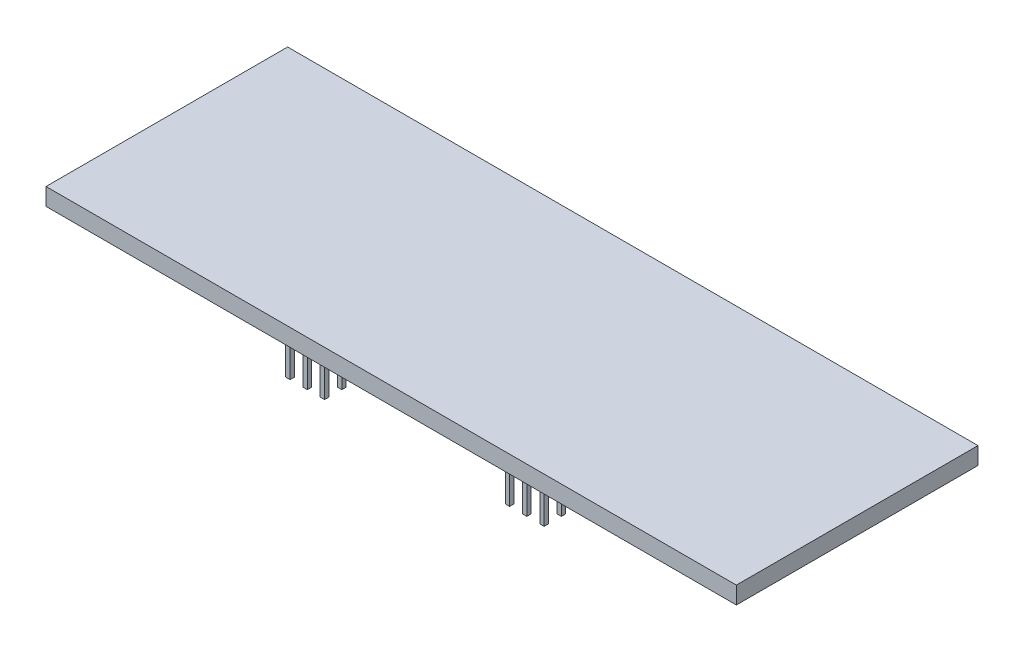
SolidWorks part; units mm, degrees
ref_plane "Front Plane" through (0, 0, 0) normal (0, 0, 1) x (1, 0, 0)
ref_plane "Top Plane" through (0, 0, 0) normal (0, 1, 0) x (1, 0, 0)
ref_plane "Right Plane" through (0, 0, 0) normal (1, 0, 0) x (0, 0, -1)
sketch "Sketch1" plane through (0, 0, 0) normal (0, 1, 0) x (1, 0, 0)
  line L0 (50.8, 35.56) -> (50.8, 0) construction
  line L1 (0, 0) -> (101.6, 0)
  line L2 (0, 0) -> (0, 35.56)
  line L3 (0, 35.56) -> (101.6, 35.56)
  line L4 (101.6, 0) -> (101.6, 35.56)
  point P5 (50.8, 35.56)
  dimension "D1" = 35.56
  dimension "D2" = 101.6
extrude "Boss-Extrude1" add sketch "Sketch1" along normal blind 2.54
sketch "Sketch2" plane through (0, 0, 0) normal (0, -1, 0) x (1, 0, 0)
  line L0 (0, -35.56) -> (0, 0) construction
  line L1 (30.8356, -2.54) -> (38.4556, -2.54)
  line L2 (30.8356, -2.54) -> (30.8356, -33.02)
  line L3 (30.8356, -33.02) -> (38.4556, -33.02)
  line L4 (38.4556, -2.54) -> (38.4556, -33.02)
  line L5 (0, 0) -> (101.6, 0) construction
  line L6 (0, 0) -> (50.8, 0) construction
  line L7 (50.8, 0) -> (50.8, -35.56) construction
  line L8 (101.6, -35.56) -> (0, -35.56) construction
  line L9 (63.1444, -2.54) -> (63.1444, -33.02)
  line L10 (70.7644, -33.02) -> (63.1444, -33.02)
  line L11 (70.7644, -2.54) -> (70.7644, -33.02)
  line L12 (70.7644, -2.54) -> (63.1444, -2.54)
  point P4 (30.8356, -17.78)
  point P5 (0, -17.78)
  point P6 (50.8, 0)
  point P9 (34.6456, -2.54)
  point P15 (25.4, 0)
  point P23 (76.2, 0)
  point P24 (66.9544, -2.54)
  point P25 (70.7644, -17.78)
  dimension "D1" = 7.62
  dimension "D2" = 30.48
  dimension "D3" = 12.3444
extrude "Boss-Extrude2" add sketch "Sketch2" along normal blind 2.54
sketch "Sketch3" plane through (0, -2.54, 0) normal (0, -1, 0) x (1, 0, 0)
  line L0 (38.4556, -2.54) -> (30.8356, -2.54) construction
  line L1 (31.7881, -3.4925) -> (32.4231, -3.4925)
  line L2 (31.7881, -3.4925) -> (31.7881, -4.1275)
  line L3 (31.7881, -4.1275) -> (32.4231, -4.1275)
  line L4 (32.4231, -3.4925) -> (32.4231, -4.1275)
  line L5 (30.8356, -2.54) -> (30.8356, -33.02) construction
  line L6 (34.3281, -3.4925) -> (34.9631, -3.4925)
  line L7 (34.3281, -3.4925) -> (34.3281, -4.1275)
  line L8 (34.3281, -4.1275) -> (34.9631, -4.1275)
  line L9 (34.9631, -3.4925) -> (34.9631, -4.1275)
  line L10 (36.8681, -3.4925) -> (37.5031, -3.4925)
  line L11 (36.8681, -3.4925) -> (36.8681, -4.1275)
  line L12 (36.8681, -4.1275) -> (37.5031, -4.1275)
  line L13 (37.5031, -3.4925) -> (37.5031, -4.1275)
  line L14 (31.7881, -6.0325) -> (32.4231, -6.0325)
  line L15 (31.7881, -6.0325) -> (31.7881, -6.6675)
  line L16 (31.7881, -6.6675) -> (32.4231, -6.6675)
  line L17 (32.4231, -6.0325) -> (32.4231, -6.6675)
  line L18 (34.3281, -6.0325) -> (34.9631, -6.0325)
  line L19 (34.3281, -6.0325) -> (34.3281, -6.6675)
  line L20 (34.3281, -6.6675) -> (34.9631, -6.6675)
  line L21 (34.9631, -6.0325) -> (34.9631, -6.6675)
  line L22 (36.8681, -6.0325) -> (37.5031, -6.0325)
  line L23 (36.8681, -6.0325) -> (36.8681, -6.6675)
  line L24 (36.8681, -6.6675) -> (37.5031, -6.6675)
  line L25 (37.5031, -6.0325) -> (37.5031, -6.6675)
  line L26 (31.7881, -8.5725) -> (32.4231, -8.5725)
  line L27 (31.7881, -8.5725) -> (31.7881, -9.2075)
  line L28 (31.7881, -9.2075) -> (32.4231, -9.2075)
  line L29 (32.4231, -8.5725) -> (32.4231, -9.2075)
  line L30 (34.3281, -8.5725) -> (34.9631, -8.5725)
  line L31 (34.3281, -8.5725) -> (34.3281, -9.2075)
  line L32 (34.3281, -9.2075) -> (34.9631, -9.2075)
  line L33 (34.9631, -8.5725) -> (34.9631, -9.2075)
  line L34 (36.8681, -8.5725) -> (37.5031, -8.5725)
  line L35 (36.8681, -8.5725) -> (36.8681, -9.2075)
  line L36 (36.8681, -9.2075) -> (37.5031, -9.2075)
  line L37 (37.5031, -8.5725) -> (37.5031, -9.2075)
  line L38 (31.7881, -11.1125) -> (32.4231, -11.1125)
  line L39 (31.7881, -11.1125) -> (31.7881, -11.7475)
  line L40 (31.7881, -11.7475) -> (32.4231, -11.7475)
  line L41 (32.4231, -11.1125) -> (32.4231, -11.7475)
  line L42 (34.3281, -11.1125) -> (34.9631, -11.1125)
  line L43 (34.3281, -11.1125) -> (34.3281, -11.7475)
  line L44 (34.3281, -11.7475) -> (34.9631, -11.7475)
  line L45 (34.9631, -11.1125) -> (34.9631, -11.7475)
  line L46 (36.8681, -11.1125) -> (37.5031, -11.1125)
  line L47 (36.8681, -11.1125) -> (36.8681, -11.7475)
  line L48 (36.8681, -11.7475) -> (37.5031, -11.7475)
  line L49 (37.5031, -11.1125) -> (37.5031, -11.7475)
  line L50 (31.7881, -13.6525) -> (32.4231, -13.6525)
  line L51 (31.7881, -13.6525) -> (31.7881, -14.2875)
  line L52 (31.7881, -14.2875) -> (32.4231, -14.2875)
  line L53 (32.4231, -13.6525) -> (32.4231, -14.2875)
  line L54 (34.3281, -13.6525) -> (34.9631, -13.6525)
  line L55 (34.3281, -13.6525) -> (34.3281, -14.2875)
  line L56 (34.3281, -14.2875) -> (34.9631, -14.2875)
  line L57 (34.9631, -13.6525) -> (34.9631, -14.2875)
  line L58 (36.8681, -13.6525) -> (37.5031, -13.6525)
  line L59 (36.8681, -13.6525) -> (36.8681, -14.2875)
  line L60 (36.8681, -14.2875) -> (37.5031, -14.2875)
  line L61 (37.5031, -13.6525) -> (37.5031, -14.2875)
  line L62 (31.7881, -16.1925) -> (32.4231, -16.1925)
  line L63 (31.7881, -16.1925) -> (31.7881, -16.8275)
  line L64 (31.7881, -16.8275) -> (32.4231, -16.8275)
  line L65 (32.4231, -16.1925) -> (32.4231, -16.8275)
  line L66 (34.3281, -16.1925) -> (34.9631, -16.1925)
  line L67 (34.3281, -16.1925) -> (34.3281, -16.8275)
  line L68 (34.3281, -16.8275) -> (34.9631, -16.8275)
  line L69 (34.9631, -16.1925) -> (34.9631, -16.8275)
  line L70 (36.8681, -16.1925) -> (37.5031, -16.1925)
  line L71 (36.8681, -16.1925) -> (36.8681, -16.8275)
  line L72 (36.8681, -16.8275) -> (37.5031, -16.8275)
  line L73 (37.5031, -16.1925) -> (37.5031, -16.8275)
  line L74 (31.7881, -18.7325) -> (32.4231, -18.7325)
  line L75 (31.7881, -18.7325) -> (31.7881, -19.3675)
  line L76 (31.7881, -19.3675) -> (32.4231, -19.3675)
  line L77 (32.4231, -18.7325) -> (32.4231, -19.3675)
  line L78 (34.3281, -18.7325) -> (34.9631, -18.7325)
  line L79 (34.3281, -18.7325) -> (34.3281, -19.3675)
  line L80 (34.3281, -19.3675) -> (34.9631, -19.3675)
  line L81 (34.9631, -18.7325) -> (34.9631, -19.3675)
  line L82 (36.8681, -18.7325) -> (37.5031, -18.7325)
  line L83 (36.8681, -18.7325) -> (36.8681, -19.3675)
  line L84 (36.8681, -19.3675) -> (37.5031, -19.3675)
  line L85 (37.5031, -18.7325) -> (37.5031, -19.3675)
  line L86 (31.7881, -21.2725) -> (32.4231, -21.2725)
  line L87 (31.7881, -21.2725) -> (31.7881, -21.9075)
  line L88 (31.7881, -21.9075) -> (32.4231, -21.9075)
  line L89 (32.4231, -21.2725) -> (32.4231, -21.9075)
  line L90 (34.3281, -21.2725) -> (34.9631, -21.2725)
  line L91 (34.3281, -21.2725) -> (34.3281, -21.9075)
  line L92 (34.3281, -21.9075) -> (34.9631, -21.9075)
  line L93 (34.9631, -21.2725) -> (34.9631, -21.9075)
  line L94 (36.8681, -21.2725) -> (37.5031, -21.2725)
  line L95 (36.8681, -21.2725) -> (36.8681, -21.9075)
  line L96 (36.8681, -21.9075) -> (37.5031, -21.9075)
  line L97 (37.5031, -21.2725) -> (37.5031, -21.9075)
  line L98 (31.7881, -23.8125) -> (32.4231, -23.8125)
  line L99 (31.7881, -23.8125) -> (31.7881, -24.4475)
  line L100 (31.7881, -24.4475) -> (32.4231, -24.4475)
  line L101 (32.4231, -23.8125) -> (32.4231, -24.4475)
  line L102 (34.3281, -23.8125) -> (34.9631, -23.8125)
  line L103 (34.3281, -23.8125) -> (34.3281, -24.4475)
  line L104 (34.3281, -24.4475) -> (34.9631, -24.4475)
  line L105 (34.9631, -23.8125) -> (34.9631, -24.4475)
  line L106 (36.8681, -23.8125) -> (37.5031, -23.8125)
  line L107 (36.8681, -23.8125) -> (36.8681, -24.4475)
  line L108 (36.8681, -24.4475) -> (37.5031, -24.4475)
  line L109 (37.5031, -23.8125) -> (37.5031, -24.4475)
  line L110 (31.7881, -26.3525) -> (32.4231, -26.3525)
  line L111 (31.7881, -26.3525) -> (31.7881, -26.9875)
  line L112 (31.7881, -26.9875) -> (32.4231, -26.9875)
  line L113 (32.4231, -26.3525) -> (32.4231, -26.9875)
  line L114 (34.3281, -26.3525) -> (34.9631, -26.3525)
  line L115 (34.3281, -26.3525) -> (34.3281, -26.9875)
  line L116 (34.3281, -26.9875) -> (34.9631, -26.9875)
  line L117 (34.9631, -26.3525) -> (34.9631, -26.9875)
  line L118 (36.8681, -26.3525) -> (37.5031, -26.3525)
  line L119 (36.8681, -26.3525) -> (36.8681, -26.9875)
  line L120 (36.8681, -26.9875) -> (37.5031, -26.9875)
  line L121 (37.5031, -26.3525) -> (37.5031, -26.9875)
  line L122 (31.7881, -28.8925) -> (32.4231, -28.8925)
  line L123 (31.7881, -28.8925) -> (31.7881, -29.5275)
  line L124 (31.7881, -29.5275) -> (32.4231, -29.5275)
  line L125 (32.4231, -28.8925) -> (32.4231, -29.5275)
  line L126 (34.3281, -28.8925) -> (34.9631, -28.8925)
  line L127 (34.3281, -28.8925) -> (34.3281, -29.5275)
  line L128 (34.3281, -29.5275) -> (34.9631, -29.5275)
  line L129 (34.9631, -28.8925) -> (34.9631, -29.5275)
  line L130 (36.8681, -28.8925) -> (37.5031, -28.8925)
  line L131 (36.8681, -28.8925) -> (36.8681, -29.5275)
  line L132 (36.8681, -29.5275) -> (37.5031, -29.5275)
  line L133 (37.5031, -28.8925) -> (37.5031, -29.5275)
  line L134 (31.7881, -31.4325) -> (32.4231, -31.4325)
  line L135 (31.7881, -31.4325) -> (31.7881, -32.0675)
  line L136 (31.7881, -32.0675) -> (32.4231, -32.0675)
  line L137 (32.4231, -31.4325) -> (32.4231, -32.0675)
  line L138 (34.3281, -31.4325) -> (34.9631, -31.4325)
  line L139 (34.3281, -31.4325) -> (34.3281, -32.0675)
  line L140 (34.3281, -32.0675) -> (34.9631, -32.0675)
  line L141 (34.9631, -31.4325) -> (34.9631, -32.0675)
  line L142 (36.8681, -31.4325) -> (37.5031, -31.4325)
  line L143 (36.8681, -31.4325) -> (36.8681, -32.0675)
  line L144 (36.8681, -32.0675) -> (37.5031, -32.0675)
  line L145 (37.5031, -31.4325) -> (37.5031, -32.0675)
  line L146 (50.8, 0) -> (50.8, -35.56) construction
  line L147 (0, 0) -> (101.6, 0) construction
  line L148 (101.6, -35.56) -> (0, -35.56) construction
  line L149 (64.0969, -31.4325) -> (64.0969, -32.0675)
  line L150 (64.7319, -32.0675) -> (64.0969, -32.0675)
  line L151 (64.7319, -31.4325) -> (64.7319, -32.0675)
  line L152 (64.7319, -31.4325) -> (64.0969, -31.4325)
  line L153 (66.6369, -31.4325) -> (66.6369, -32.0675)
  line L154 (67.2719, -32.0675) -> (66.6369, -32.0675)
  line L155 (67.2719, -31.4325) -> (67.2719, -32.0675)
  line L156 (67.2719, -31.4325) -> (66.6369, -31.4325)
  line L157 (69.1769, -31.4325) -> (69.1769, -32.0675)
  line L158 (69.8119, -32.0675) -> (69.1769, -32.0675)
  line L159 (69.8119, -31.4325) -> (69.8119, -32.0675)
  line L160 (69.8119, -31.4325) -> (69.1769, -31.4325)
  line L161 (64.0969, -28.8925) -> (64.0969, -29.5275)
  line L162 (64.7319, -29.5275) -> (64.0969, -29.5275)
  line L163 (64.7319, -28.8925) -> (64.7319, -29.5275)
  line L164 (64.7319, -28.8925) -> (64.0969, -28.8925)
  line L165 (66.6369, -28.8925) -> (66.6369, -29.5275)
  line L166 (67.2719, -29.5275) -> (66.6369, -29.5275)
  line L167 (67.2719, -28.8925) -> (67.2719, -29.5275)
  line L168 (67.2719, -28.8925) -> (66.6369, -28.8925)
  line L169 (69.1769, -28.8925) -> (69.1769, -29.5275)
  line L170 (69.8119, -29.5275) -> (69.1769, -29.5275)
  line L171 (69.8119, -28.8925) -> (69.8119, -29.5275)
  line L172 (69.8119, -28.8925) -> (69.1769, -28.8925)
  line L173 (64.0969, -26.3525) -> (64.0969, -26.9875)
  line L174 (64.7319, -26.9875) -> (64.0969, -26.9875)
  line L175 (64.7319, -26.3525) -> (64.7319, -26.9875)
  line L176 (64.7319, -26.3525) -> (64.0969, -26.3525)
  line L177 (66.6369, -26.3525) -> (66.6369, -26.9875)
  line L178 (67.2719, -26.9875) -> (66.6369, -26.9875)
  line L179 (67.2719, -26.3525) -> (67.2719, -26.9875)
  line L180 (67.2719, -26.3525) -> (66.6369, -26.3525)
  line L181 (69.1769, -26.3525) -> (69.1769, -26.9875)
  line L182 (69.8119, -26.9875) -> (69.1769, -26.9875)
  line L183 (69.8119, -26.3525) -> (69.8119, -26.9875)
  line L184 (69.8119, -26.3525) -> (69.1769, -26.3525)
  line L185 (64.0969, -23.8125) -> (64.0969, -24.4475)
  line L186 (64.7319, -24.4475) -> (64.0969, -24.4475)
  line L187 (64.7319, -23.8125) -> (64.7319, -24.4475)
  line L188 (64.7319, -23.8125) -> (64.0969, -23.8125)
  line L189 (66.6369, -23.8125) -> (66.6369, -24.4475)
  line L190 (67.2719, -24.4475) -> (66.6369, -24.4475)
  line L191 (67.2719, -23.8125) -> (67.2719, -24.4475)
  line L192 (67.2719, -23.8125) -> (66.6369, -23.8125)
  line L193 (69.1769, -23.8125) -> (69.1769, -24.4475)
  line L194 (69.8119, -24.4475) -> (69.1769, -24.4475)
  line L195 (69.8119, -23.8125) -> (69.8119, -24.4475)
  line L196 (69.8119, -23.8125) -> (69.1769, -23.8125)
  line L197 (64.0969, -21.2725) -> (64.0969, -21.9075)
  line L198 (64.7319, -21.9075) -> (64.0969, -21.9075)
  line L199 (64.7319, -21.2725) -> (64.7319, -21.9075)
  line L200 (64.7319, -21.2725) -> (64.0969, -21.2725)
  line L201 (66.6369, -21.2725) -> (66.6369, -21.9075)
  line L202 (67.2719, -21.9075) -> (66.6369, -21.9075)
  line L203 (67.2719, -21.2725) -> (67.2719, -21.9075)
  line L204 (67.2719, -21.2725) -> (66.6369, -21.2725)
  line L205 (69.1769, -21.2725) -> (69.1769, -21.9075)
  line L206 (69.8119, -21.9075) -> (69.1769, -21.9075)
  line L207 (69.8119, -21.2725) -> (69.8119, -21.9075)
  line L208 (69.8119, -21.2725) -> (69.1769, -21.2725)
  line L209 (64.0969, -18.7325) -> (64.0969, -19.3675)
  line L210 (64.7319, -19.3675) -> (64.0969, -19.3675)
  line L211 (64.7319, -18.7325) -> (64.7319, -19.3675)
  line L212 (64.7319, -18.7325) -> (64.0969, -18.7325)
  line L213 (66.6369, -18.7325) -> (66.6369, -19.3675)
  line L214 (67.2719, -19.3675) -> (66.6369, -19.3675)
  line L215 (67.2719, -18.7325) -> (67.2719, -19.3675)
  line L216 (67.2719, -18.7325) -> (66.6369, -18.7325)
  line L217 (69.1769, -18.7325) -> (69.1769, -19.3675)
  line L218 (69.8119, -19.3675) -> (69.1769, -19.3675)
  line L219 (69.8119, -18.7325) -> (69.8119, -19.3675)
  line L220 (69.8119, -18.7325) -> (69.1769, -18.7325)
  line L221 (64.0969, -16.1925) -> (64.0969, -16.8275)
  line L222 (64.7319, -16.8275) -> (64.0969, -16.8275)
  line L223 (64.7319, -16.1925) -> (64.7319, -16.8275)
  line L224 (64.7319, -16.1925) -> (64.0969, -16.1925)
  line L225 (66.6369, -16.1925) -> (66.6369, -16.8275)
  line L226 (67.2719, -16.8275) -> (66.6369, -16.8275)
  line L227 (67.2719, -16.1925) -> (67.2719, -16.8275)
  line L228 (67.2719, -16.1925) -> (66.6369, -16.1925)
  line L229 (69.1769, -16.1925) -> (69.1769, -16.8275)
  line L230 (69.8119, -16.8275) -> (69.1769, -16.8275)
  line L231 (69.8119, -16.1925) -> (69.8119, -16.8275)
  line L232 (69.8119, -16.1925) -> (69.1769, -16.1925)
  line L233 (64.0969, -13.6525) -> (64.0969, -14.2875)
  line L234 (64.7319, -14.2875) -> (64.0969, -14.2875)
  line L235 (64.7319, -13.6525) -> (64.7319, -14.2875)
  line L236 (64.7319, -13.6525) -> (64.0969, -13.6525)
  line L237 (66.6369, -13.6525) -> (66.6369, -14.2875)
  line L238 (67.2719, -14.2875) -> (66.6369, -14.2875)
  line L239 (67.2719, -13.6525) -> (67.2719, -14.2875)
  line L240 (67.2719, -13.6525) -> (66.6369, -13.6525)
  line L241 (69.1769, -13.6525) -> (69.1769, -14.2875)
  line L242 (69.8119, -14.2875) -> (69.1769, -14.2875)
  line L243 (69.8119, -13.6525) -> (69.8119, -14.2875)
  line L244 (69.8119, -13.6525) -> (69.1769, -13.6525)
  line L245 (64.0969, -11.1125) -> (64.0969, -11.7475)
  line L246 (64.7319, -11.7475) -> (64.0969, -11.7475)
  line L247 (64.7319, -11.1125) -> (64.7319, -11.7475)
  line L248 (64.7319, -11.1125) -> (64.0969, -11.1125)
  line L249 (66.6369, -11.1125) -> (66.6369, -11.7475)
  line L250 (67.2719, -11.7475) -> (66.6369, -11.7475)
  line L251 (67.2719, -11.1125) -> (67.2719, -11.7475)
  line L252 (67.2719, -11.1125) -> (66.6369, -11.1125)
  line L253 (69.1769, -11.1125) -> (69.1769, -11.7475)
  line L254 (69.8119, -11.7475) -> (69.1769, -11.7475)
  line L255 (69.8119, -11.1125) -> (69.8119, -11.7475)
  line L256 (69.8119, -11.1125) -> (69.1769, -11.1125)
  line L257 (64.0969, -8.5725) -> (64.0969, -9.2075)
  line L258 (64.7319, -9.2075) -> (64.0969, -9.2075)
  line L259 (64.7319, -8.5725) -> (64.7319, -9.2075)
  line L260 (64.7319, -8.5725) -> (64.0969, -8.5725)
  line L261 (66.6369, -8.5725) -> (66.6369, -9.2075)
  line L262 (67.2719, -9.2075) -> (66.6369, -9.2075)
  line L263 (67.2719, -8.5725) -> (67.2719, -9.2075)
  line L264 (67.2719, -8.5725) -> (66.6369, -8.5725)
  line L265 (69.1769, -8.5725) -> (69.1769, -9.2075)
  line L266 (69.8119, -9.2075) -> (69.1769, -9.2075)
  line L267 (69.8119, -8.5725) -> (69.8119, -9.2075)
  line L268 (69.8119, -8.5725) -> (69.1769, -8.5725)
  line L269 (64.0969, -6.0325) -> (64.0969, -6.6675)
  line L270 (64.7319, -6.6675) -> (64.0969, -6.6675)
  line L271 (64.7319, -6.0325) -> (64.7319, -6.6675)
  line L272 (64.7319, -6.0325) -> (64.0969, -6.0325)
  line L273 (66.6369, -6.0325) -> (66.6369, -6.6675)
  line L274 (67.2719, -6.6675) -> (66.6369, -6.6675)
  line L275 (67.2719, -6.0325) -> (67.2719, -6.6675)
  line L276 (67.2719, -6.0325) -> (66.6369, -6.0325)
  line L277 (69.1769, -6.0325) -> (69.1769, -6.6675)
  line L278 (69.8119, -6.6675) -> (69.1769, -6.6675)
  line L279 (69.8119, -6.0325) -> (69.8119, -6.6675)
  line L280 (69.8119, -6.0325) -> (69.1769, -6.0325)
  line L281 (64.0969, -3.4925) -> (64.0969, -4.1275)
  line L282 (64.7319, -4.1275) -> (64.0969, -4.1275)
  line L283 (64.7319, -3.4925) -> (64.7319, -4.1275)
  line L284 (64.7319, -3.4925) -> (64.0969, -3.4925)
  line L285 (66.6369, -3.4925) -> (66.6369, -4.1275)
  line L286 (67.2719, -4.1275) -> (66.6369, -4.1275)
  line L287 (67.2719, -3.4925) -> (67.2719, -4.1275)
  line L288 (67.2719, -3.4925) -> (66.6369, -3.4925)
  line L289 (69.1769, -3.4925) -> (69.1769, -4.1275)
  line L290 (69.8119, -4.1275) -> (69.1769, -4.1275)
  line L291 (69.8119, -3.4925) -> (69.8119, -4.1275)
  line L292 (69.8119, -3.4925) -> (69.1769, -3.4925)
  dimension "D1" = 0.635
  dimension "D2" = 0.635
  dimension "D3" = 0.9525
  dimension "D4" = 0.9525
  dimension "D5" = 3
  dimension "D6" = 12
extrude "Boss-Extrude3" add sketch "Sketch3" along normal blind 5.08
